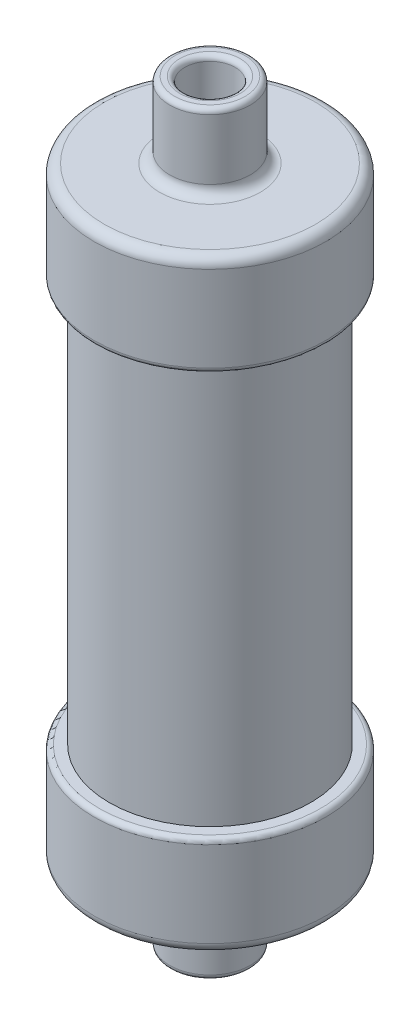
SolidWorks part; units mm, degrees
ref_plane "Alzado" through (0, 0, 0) normal (0, 0, 1) x (1, 0, 0)
ref_plane "Planta" through (0, 0, 0) normal (0, 1, 0) x (1, 0, 0)
ref_plane "Vista lateral" through (0, 0, 0) normal (1, 0, 0) x (0, 0, -1)
sketch "Croquis1" plane through (0, 0, 0) normal (0, 1, 0) x (1, 0, 0)
  circle A0 centre (0, 0) radius 20
  dimension "D1" = 40
extrude "Extruir-Lámina1" add sketch "Croquis1" along normal blind 50 and the other way blind 50 thin thin type one direction reverse wall 3
sketch "Croquis2" plane through (0, 50, 0) normal (0, 1, 0) x (1, 0, 0)
  circle A1 centre (0, 0) radius 20 construction
  circle A2 centre (0, 0) radius 23
  circle A3 centre (0, 0) radius 23
  circle A4 centre (0, 0) radius 20
  dimension "D1" = 3
extrude "Extruir1" add sketch "Croquis2" against normal blind 10 separate body
sketch "Croquis3" plane through (0, 50, 0) normal (0, 1, 0) x (1, 0, 0)
  circle A0 centre (0, 0) radius 23 construction
  circle A1 centre (0, 0) radius 23
extrude "Extruir2" add sketch "Croquis3" along normal blind 10
sketch "Croquis4" plane through (0, 60, 0) normal (0, 1, 0) x (1, 0, 0)
  circle A0 centre (0, 0) radius 5
  circle A1 centre (0, 0) radius 8
  dimension "D1" = 10
  dimension "D2" = 3
extrude "Extruir3" add sketch "Croquis4" along normal blind 15
sketch "Croquis5" plane through (0, 60, 0) normal (0, 1, 0) x (1, 0, 0)
  circle A0 centre (0, 0) radius 5 construction
  circle A1 centre (0, 0) radius 5
extrude "Extruir4" cut sketch "Croquis5" against normal blind 20
fillet "Redondeo1" radius 2 2 edges at (0, 60, 8) (0, 60, 23)
fillet "Redondeo2" radius 1 3 edges at (0, 40, 23) (0, 75, 5) (0, 75, 8)
mirror "Simetría1" about plane through (0, 0, 0) normal (0, 1, 0) of bodies 105
